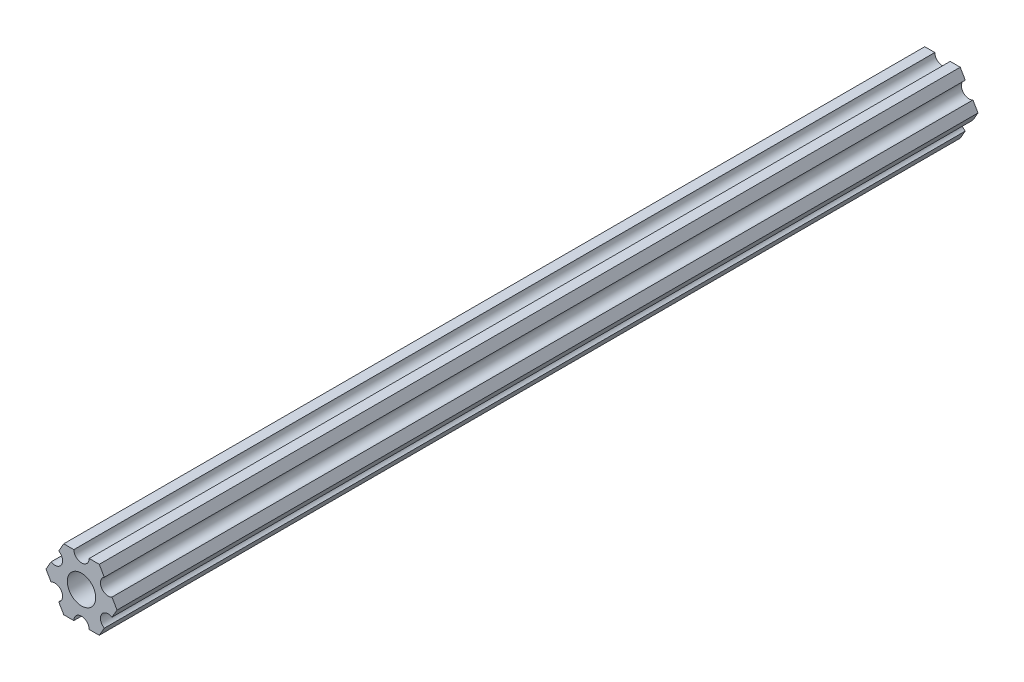
SolidWorks part; units mm, degrees
ref_plane "Front Plane" through (0, 0, 0) normal (0, 0, 1) x (1, 0, 0)
ref_plane "Top Plane" through (0, 0, 0) normal (0, 1, 0) x (1, 0, 0)
ref_plane "Right Plane" through (0, 0, 0) normal (1, 0, 0) x (0, 0, -1)
sketch "Sketch1" plane through (0, 0, 0) normal (0, 0, 1) x (1, 0, 0)
  line L0 (-4.7055, -4.5498) -> (-3.6662, -6.35)
  line L1 (7.3323, 0) -> (6.293, 1.8002)
  line L2 (3.6662, 6.35) -> (1.5875, 6.35)
  line L3 (-3.6662, 6.35) -> (-4.7055, 4.5498)
  line L4 (-7.3323, 0) -> (-6.293, -1.8002)
  line L5 (-3.6662, -6.35) -> (-1.5875, -6.35)
  line L6 (3.6662, -6.35) -> (4.7055, -4.5498)
  line L7 (-6.293, 1.8002) -> (-7.3323, 0)
  line L8 (-1.5875, 6.35) -> (-3.6662, 6.35)
  line L9 (4.7055, 4.5498) -> (3.6662, 6.35)
  line L10 (6.293, -1.8002) -> (7.3323, 0)
  line L11 (1.5875, -6.35) -> (3.6662, -6.35)
  circle A0 centre (0, 0) radius 6.35 construction
  circle A1 centre (0, 0) radius 2.9337
  arc A2 (-1.5875, 6.35) -> (1.5875, 6.35) centre (0, 6.35) ccw
  arc A3 (4.7055, 4.5498) -> (6.293, 1.8002) centre (5.4993, 3.175) ccw
  arc A4 (6.293, -1.8002) -> (4.7055, -4.5498) centre (5.4993, -3.175) ccw
  arc A5 (1.5875, -6.35) -> (-1.5875, -6.35) centre (0, -6.35) ccw
  arc A6 (-4.7055, -4.5498) -> (-6.293, -1.8002) centre (-5.4993, -3.175) ccw
  arc A7 (-6.293, 1.8002) -> (-4.7055, 4.5498) centre (-5.4993, 3.175) ccw
  point P24 (0, 0)
  dimension "D1" = 12.7
  dimension "D2" = 5.8674
  dimension "D3" = 3.175
extrude "Boss-Extrude1" add sketch "Sketch1" along normal blind 177.8
